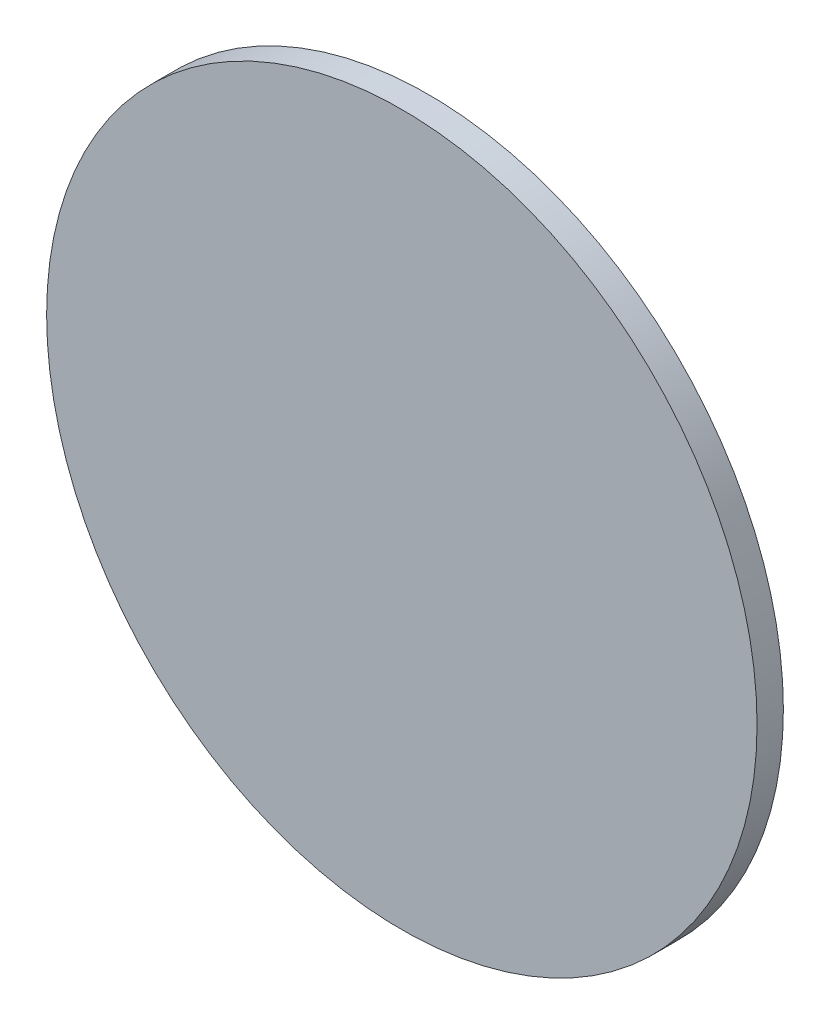
SolidWorks part; units mm, degrees
ref_plane "Front Plane" through (0, 0, 0) normal (0, 0, 1) x (1, 0, 0)
ref_plane "Top Plane" through (0, 0, 0) normal (0, 1, 0) x (1, 0, 0)
ref_plane "Right Plane" through (0, 0, 0) normal (1, 0, 0) x (0, 0, -1)
sketch "Sketch1" plane through (0, 0, 0) normal (0, 0, 1) x (1, 0, 0)
  circle A0 centre (0, 0) radius 13.5
  dimension "D1" = 27
extrude "Boss-Extrude1" add sketch "Sketch1" along normal blind 1
